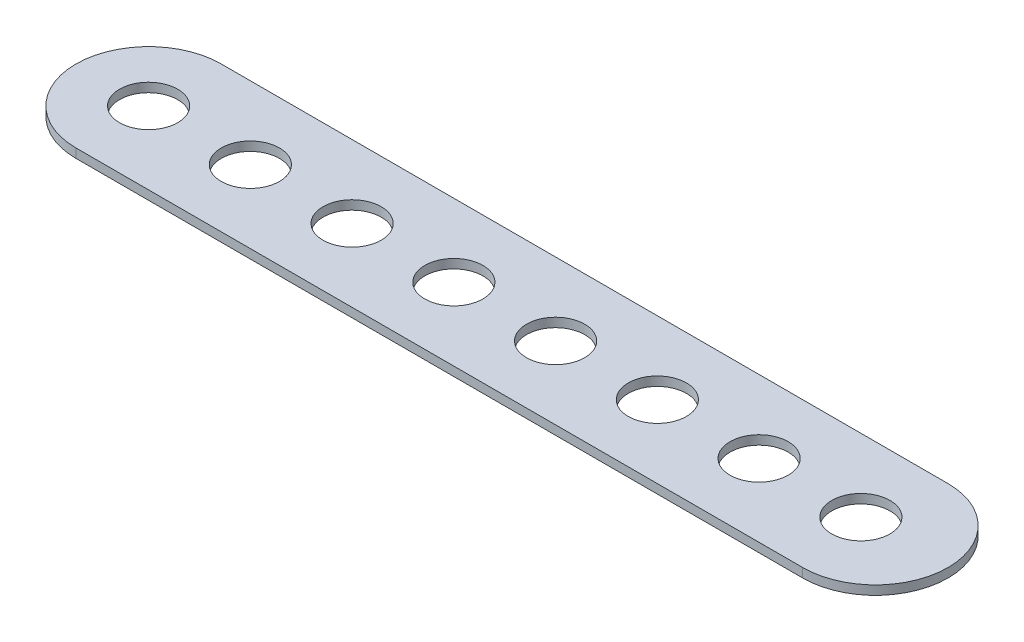
SolidWorks part; units mm, degrees
ref_plane "Front Plane" through (0, 0, 0) normal (0, 0, 1) x (1, 0, 0)
ref_plane "Top Plane" through (0, 0, 0) normal (0, 1, 0) x (1, 0, 0)
ref_plane "Right Plane" through (0, 0, 0) normal (1, 0, 0) x (0, 0, -1)
sketch "Sketch1" plane through (0, 0, 0) normal (0, 1, 0) x (1, 0, 0)
  line L0 (0, 0) -> (-254, 0) construction
  line L1 (0, 25.4) -> (-254, 25.4)
  line L2 (0, -25.4) -> (-254, -25.4)
  arc A0 (0, -25.4) -> (0, 25.4) centre (0, 0) ccw
  arc A1 (-254, 25.4) -> (-254, -25.4) centre (-254, 0) ccw
  dimension "D1" = 50.8
  dimension "D2" = 254
extrude "Boss-Extrude1" add sketch "Sketch1" along normal blind 3.175
sketch "Sketch3" plane through (0, 3.175, 0) normal (0, 1, 0) x (1, 0, 0)
  circle A1 centre (-254, 0) radius 10.16
  dimension "D1" = 20.32
extrude "Cut-Extrude1" cut sketch "Sketch3" against normal through all
pattern_linear "LPattern1" count 8 spacing 35.56 along (1, 0, 0) of "Cut-Extrude1"
